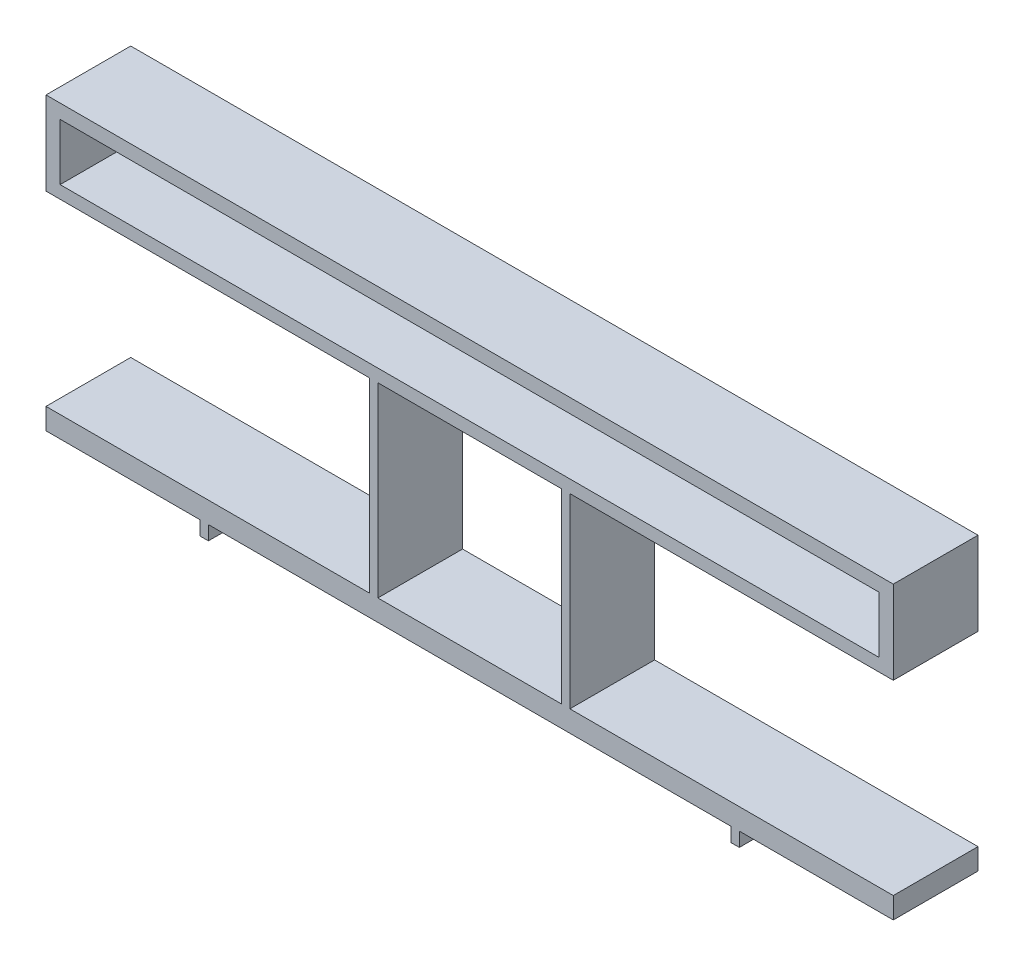
SolidWorks part; units mm, degrees
ref_plane "Front Plane" through (0, 0, 0) normal (0, 0, 1) x (1, 0, 0)
ref_plane "Top Plane" through (0, 0, 0) normal (0, 1, 0) x (1, 0, 0)
ref_plane "Right Plane" through (0, 0, 0) normal (1, 0, 0) x (0, 0, -1)
sketch "Sketch2" plane through (0, 0, 0) normal (0, 0, 1) x (1, 0, 0)
  line L1 (-12.2386, 3.1875) -> (287.7614, 3.1875)
  line L2 (-12.2386, 3.1875) -> (-12.2386, -4.3125)
  line L3 (-12.2386, -4.3125) -> (287.7614, -4.3125)
  line L4 (287.7614, 3.1875) -> (287.7614, -4.3125)
  dimension "D1" = 7.5
  dimension "D2" = 300
extrude "Boss-Extrude1" add sketch "Sketch2" along normal blind 30
sketch "Sketch3" plane through (0, -4.3125, 0) normal (0, -1, 0) x (1, 0, 0)
  line L0 (-12.2386, 0) -> (287.7614, 0) construction
  line L1 (233.2614, 0) -> (230.2614, 0)
  line L2 (233.2614, 0) -> (233.2614, 30)
  line L3 (233.2614, 30) -> (230.2614, 30)
  line L4 (230.2614, 0) -> (230.2614, 30)
  line L5 (-12.2386, 30) -> (287.7614, 30) construction
  line L7 (287.7614, 30) -> (287.7614, 0) construction
  line L8 (45.2614, 0) -> (42.2614, 0)
  line L9 (45.2614, 30) -> (42.2614, 30)
  line L10 (42.2614, 0) -> (42.2614, 30)
  line L11 (45.2614, 0) -> (45.2614, 30)
  line L12 (-12.2386, 30) -> (-12.2386, 0) construction
  dimension "D1" = 3
  dimension "D2" = 57.5
  dimension "D3" = 57.5
extrude "Boss-Extrude2" add sketch "Sketch3" along normal blind 5
sketch "Sketch4" plane through (0, 3.1875, 0) normal (0, 1, 0) x (1, 0, 0)
  line L0 (287.7614, 0) -> (-12.2386, 0) construction
  line L1 (170.2614, 0) -> (173.2614, 0)
  line L2 (170.2614, 0) -> (170.2614, -30)
  line L3 (170.2614, -30) -> (173.2614, -30)
  line L4 (173.2614, 0) -> (173.2614, -30)
  line L5 (287.7614, -30) -> (-12.2386, -30) construction
  line L6 (102.2614, 0) -> (105.2614, 0)
  line L7 (102.2614, -30) -> (105.2614, -30)
  line L8 (105.2614, 0) -> (105.2614, -30)
  line L9 (102.2614, 0) -> (102.2614, -30)
  line L11 (287.7614, -30) -> (287.7614, 0) construction
  dimension "D1" = 3
  dimension "D2" = 65
  dimension "D3" = 117.5
extrude "Boss-Extrude3" add sketch "Sketch4" along normal blind 66
sketch "Sketch5" plane through (0, 69.1875, 0) normal (0, 1, 0) x (1, 0, 0)
  line L0 (105.2614, 0) -> (102.2614, 0) construction
  line L1 (-12.2386, 0) -> (287.7614, 0)
  line L2 (-12.2386, 0) -> (-12.2386, -30)
  line L3 (-12.2386, -30) -> (287.7614, -30)
  line L4 (287.7614, 0) -> (287.7614, -30)
  point P6 (103.7614, 0)
  dimension "D1" = 300
  dimension "D2" = 30
  dimension "D3" = 0
  dimension "D4" = 117.5
extrude "Boss-Extrude4" add sketch "Sketch5" along normal blind 29.5
sketch "Sketch6" plane through (0, 0, 0) normal (0, 0, -1) x (-1, 0, 0)
  line L0 (-287.7614, 98.6875) -> (-287.7614, 69.1875) construction
  line L1 (-282.7614, 93.6875) -> (7.2386, 93.6875)
  line L2 (-282.7614, 93.6875) -> (-282.7614, 73.6875)
  line L3 (-282.7614, 73.6875) -> (7.2386, 73.6875)
  line L4 (7.2386, 93.6875) -> (7.2386, 73.6875)
  line L5 (-287.7614, 98.6875) -> (12.2386, 98.6875) construction
  dimension "D1" = 290
  dimension "D2" = 5
  dimension "D3" = 20
  dimension "D4" = 5
extrude "Cut-Extrude1" cut sketch "Sketch6" against normal through all
